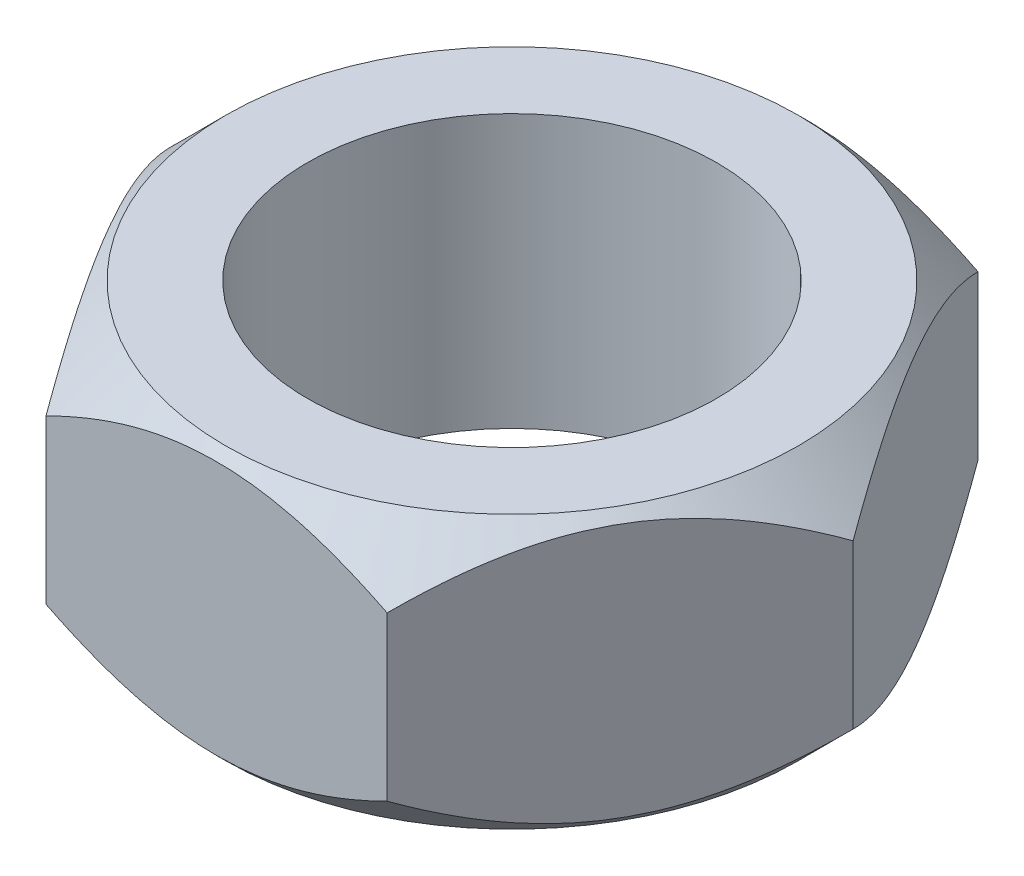
SolidWorks part; units mm, degrees
material "Alloy Steel"
ref_plane "Front Plane" through (0, 0, 0) normal (0, 0, 1) x (1, 0, 0)
ref_plane "Top Plane" through (0, 0, 0) normal (0, 1, 0) x (1, 0, 0)
ref_plane "Right Plane" through (0, 0, 0) normal (1, 0, 0) x (0, 0, -1)
sketch "Sketch1" plane through (0, 0, 0) normal (0, 1, 0) x (1, 0, 0)
  line L1 (-4.766, 8.255) -> (-9.5321, 0)
  line L2 (-9.5321, 0) -> (-4.766, -8.255)
  line L3 (-4.766, -8.255) -> (4.766, -8.255)
  line L4 (4.766, -8.255) -> (9.5321, 0)
  line L5 (9.5321, 0) -> (4.766, 8.255)
  line L6 (4.766, 8.255) -> (-4.766, 8.255)
  circle A0 centre (0, 0) radius 5.715
  circle A1 centre (0, 0) radius 8.255 construction
  dimension "D1" = 11.43
  dimension "D2" = 2.54
extrude "Boss-Extrude1" add sketch "Sketch1" along normal blind 7.62
sketch "Sketch2" plane through (0, 0, 0) normal (1, 0, 0) x (0, 0, -1)
  line L0 (-8.001, 7.62) -> (-11.811, 3.81)
  line L1 (-8.255, 7.62) -> (0, 7.62) construction
  line L2 (-11.811, 3.81) -> (-8.001, 0)
  line L3 (-8.255, 0) -> (0, 0) construction
  line L4 (-8.001, 0) -> (-14.351, 0)
  line L5 (-14.351, 0) -> (-14.351, 7.62)
  line L6 (-14.351, 7.62) -> (-8.001, 7.62)
  line L7 (-8.255, 7.62) -> (-8.255, 0) construction
  line L8 (0, 7.62) -> (0, 0) construction
  dimension "D1" = 2.54
  dimension "D2" = 0.254
  dimension "D3" = 45
revolve "Cut-Revolve1" cut sketch "Sketch2" angle 360 about L8
